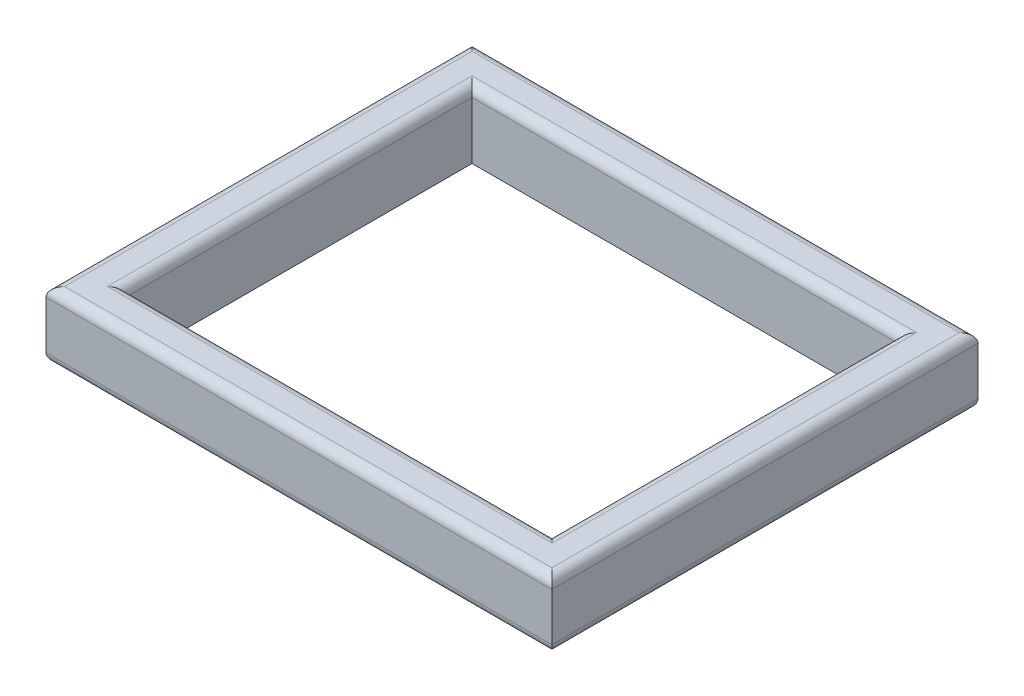
SolidWorks part; units mm, degrees
material "ABS"
ref_plane "Front Plane" through (0, 0, 0) normal (0, 0, 1) x (1, 0, 0)
ref_plane "Top Plane" through (0, 0, 0) normal (0, 1, 0) x (1, 0, 0)
ref_plane "Right Plane" through (0, 0, 0) normal (1, 0, 0) x (0, 0, -1)
sketch "Sketch1" plane through (0, 0, 0) normal (0, 1, 0) x (1, 0, 0)
  line L1 (-406.4, 330.2) -> (406.4, 330.2)
  line L2 (-406.4, 330.2) -> (-406.4, -330.2)
  line L3 (-406.4, -330.2) -> (406.4, -330.2)
  line L4 (406.4, 330.2) -> (406.4, -330.2)
  line L5 (-406.4, 330.2) -> (406.4, -330.2) construction
  line L6 (-406.4, -330.2) -> (406.4, 330.2) construction
  line L7 (482.6, 406.4) -> (-482.6, 406.4)
  line L8 (482.6, 406.4) -> (482.6, -406.4)
  line L9 (482.6, -406.4) -> (-482.6, -406.4)
  line L10 (-482.6, 406.4) -> (-482.6, -406.4)
  line L11 (482.6, 406.4) -> (-482.6, -406.4) construction
  line L12 (482.6, -406.4) -> (-482.6, 406.4) construction
  point P0 (0, 0)
  point P6 (0, 0)
  dimension "D1" = 812.8
  dimension "D2" = 660.4
  dimension "D3" = 76.2
  dimension "D4" = 76.2
extrude "Boss-Extrude1" add sketch "Sketch1" along normal blind 127
fillet "Fillet1" radius 17.78 12 edges at (0, 0, 406.4) (482.6, 0, 0) (0, 0, -406.4) (-482.6, 0, 0) (0, 127, -330.2) (-406.4, 127, 0) (0, 127, 330.2) (406.4, 127, 0) (0, 127, -406.4) (482.6, 127, 0) (0, 127, 406.4) (-482.6, 127, 0)
